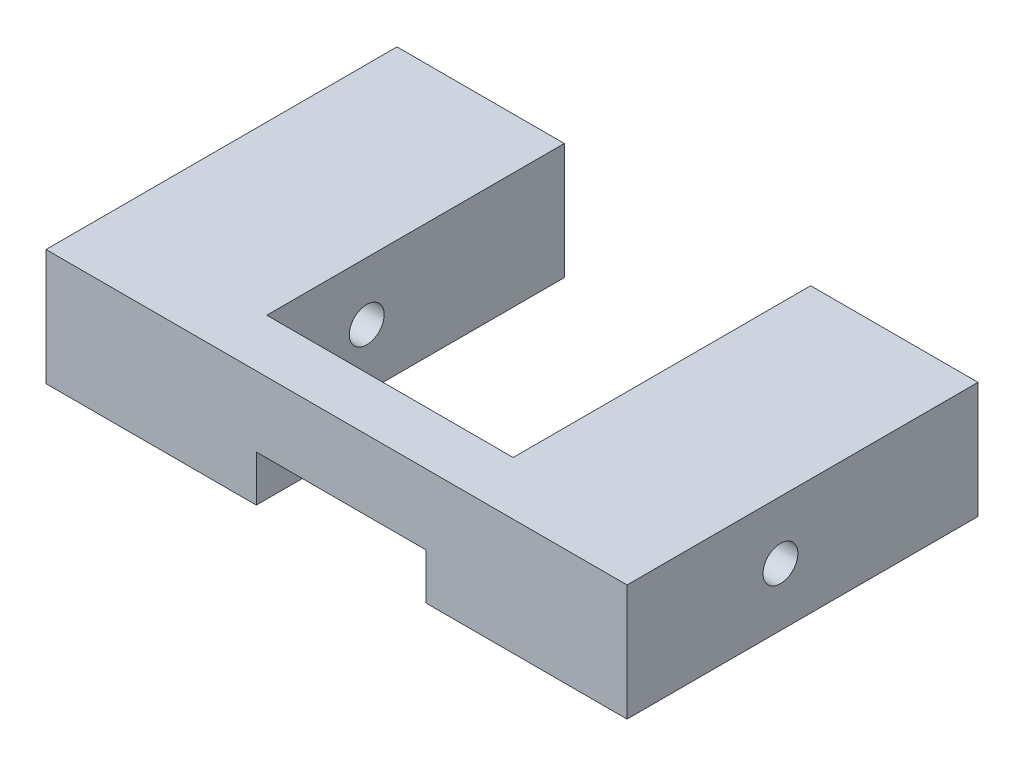
SolidWorks part; units mm, degrees
ref_plane "Front Plane" through (0, 0, 0) normal (0, 0, 1) x (1, 0, 0)
ref_plane "Top Plane" through (0, 0, 0) normal (0, 1, 0) x (1, 0, 0)
ref_plane "Right Plane" through (0, 0, 0) normal (1, 0, 0) x (0, 0, -1)
sketch "Sketch1" plane through (0, 0, 0) normal (0, 1, 0) x (1, 0, 0)
  line L1 (-12.5, -4.8) -> (12.5, -4.8)
  line L2 (-12.5, -4.8) -> (-12.5, 4.8)
  line L3 (-12.5, 4.8) -> (12.5, 4.8)
  line L4 (12.5, -4.8) -> (12.5, 4.8)
  line L5 (-12.5, -4.8) -> (12.5, 4.8) construction
  line L6 (-12.5, 4.8) -> (12.5, -4.8) construction
  line L7 (-2.5, 4.8) -> (7.5, 4.8)
  point P0 (0, 0)
  dimension "D1" = 25
extrude "Boss-Extrude1" add sketch "Sketch1" along normal blind 5 contours L2 L3 L4 L1
sketch "Sketch2" plane through (0, 5, 0) normal (0, 1, 0) x (1, 0, 0)
  line L0 (-12.5, 4.8) -> (12.5, 4.8) construction
  line L1 (-5.3, 4.8) -> (5.3, 4.8)
  line L2 (-5.3, 4.8) -> (-5.3, -2.5)
  line L3 (-5.3, -2.5) -> (5.3, -2.5)
  line L4 (5.3, 4.8) -> (5.3, -2.5)
  line L5 (-12.5, -4.8) -> (-12.5, 4.8) construction
  line L7 (-12.5, -4.8) -> (12.5, -4.8) construction
  dimension "D1" = 10.6
  dimension "D2" = 7.2
  dimension "D4" = 2.3
extrude "Cut-Extrude1" cut sketch "Sketch2" against normal blind 10
sketch "Sketch3" plane through (0, 0, 2.5) normal (0, 0, -1) x (-1, 0, 0)
  line L0 (5.3, 0) -> (-5.3, 0) construction
  line L1 (-3.85, 0) -> (3.45, 0)
  line L2 (-3.85, 0) -> (-3.85, 1.98)
  line L3 (-3.85, 1.98) -> (3.45, 1.98)
  line L4 (3.45, 0) -> (3.45, 1.98)
  line L7 (-5.3, 0) -> (-5.3, 5) construction
  line L8 (5.3, 0) -> (5.3, 5) construction
  dimension "D1" = 7.3
  dimension "D2" = 1.45
  dimension "D3" = 1.98
  dimension "D4" = 1.85
extrude "Cut-Extrude2" cut sketch "Sketch3" against normal blind 10
sketch "Sketch4" plane through (-12.5, 0, 0) normal (-1, 0, 0) x (0, 0, 1)
  line L0 (-4.8, 5) -> (-4.8, 0) construction
  circle A0 centre (-1.8, 2.5) radius 0.75
  dimension "D1" = 1.5
  dimension "D2" = 3
extrude "Cut-Extrude3" cut sketch "Sketch4" against normal blind 26
sketch "Sketch6" plane through (0, 0, -4.8) normal (0, 0, -1) x (-1, 0, 0)
  line L1 (-12.5, 5) -> (-5.3, 5)
  line L2 (-12.5, 5) -> (-12.5, 0)
  line L3 (-12.5, 0) -> (-5.3, 0)
  line L4 (-5.3, 5) -> (-5.3, 0)
  line L5 (5.3, 5) -> (12.5, 5)
  line L6 (5.3, 5) -> (5.3, 0)
  line L7 (5.3, 0) -> (12.5, 0)
  line L8 (12.5, 5) -> (12.5, 0)
extrude "Boss-Extrude3" add sketch "Sketch6" along normal blind 5.5
